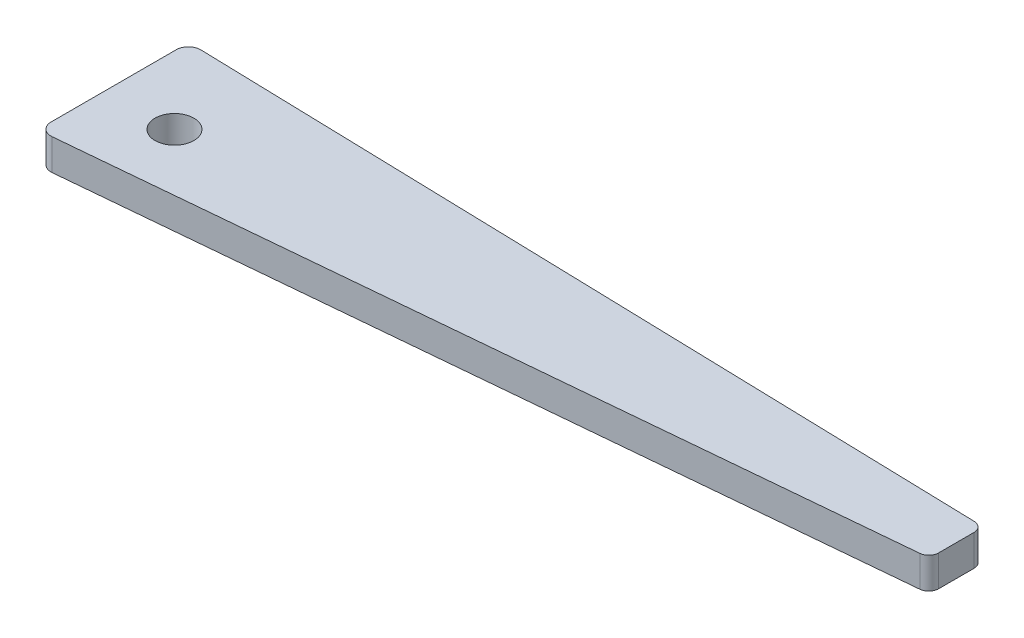
SolidWorks part; units mm, degrees
ref_plane "Front Plane" through (0, 0, 0) normal (0, 0, 1) x (1, 0, 0)
ref_plane "Top Plane" through (0, 0, 0) normal (0, 1, 0) x (1, 0, 0)
ref_plane "Right Plane" through (0, 0, 0) normal (1, 0, 0) x (0, 0, -1)
sketch "Sketch1" plane through (0, 0, 0) normal (0, 1, 0) x (1, 0, 0)
  line L0 (0.6878, 0.0632) -> (41.5458, 3.8198)
  line L1 (42, 4.3177) -> (42, 6.14)
  line L2 (41.5136, 6.6398) -> (0.6472, 7.7531)
  line L3 (0, 7.1232) -> (0, 0.6907)
  arc A0 (41.5458, 3.8198) -> (42, 4.3177) centre (41.5, 4.3177) ccw
  arc A1 (42, 6.14) -> (41.5136, 6.6398) centre (41.5, 6.14) ccw
  arc A2 (0.6878, 0.0632) -> (0, 0.6907) centre (0.6301, 0.6907) cw
  arc A3 (0.6472, 7.7531) -> (0, 7.1232) centre (0.6301, 7.1232) ccw
  point P11 (0, 0)
  dimension "D2" = 0.5
  dimension "D3" = 0.6301
  dimension "D1" = 42
extrude "Boss-Extrude1" add sketch "Sketch1" along normal blind 1.6
sketch "Sketch2" plane through (0, 1.6, 0) normal (0, 1, 0) x (1, 0, 0)
  line L1 (0, 7.1232) -> (0, 0.6907) construction
  line L2 (0.6878, 0.0632) -> (41.5458, 3.8198) construction
  circle A0 centre (3.5, 3.5353) radius 1
  point P6 (0, 3.907)
  dimension "D1" = 2
  dimension "D2" = 3.5
  dimension "D3" = 3.2
extrude "Cut-Extrude1" cut sketch "Sketch2" against normal through all
